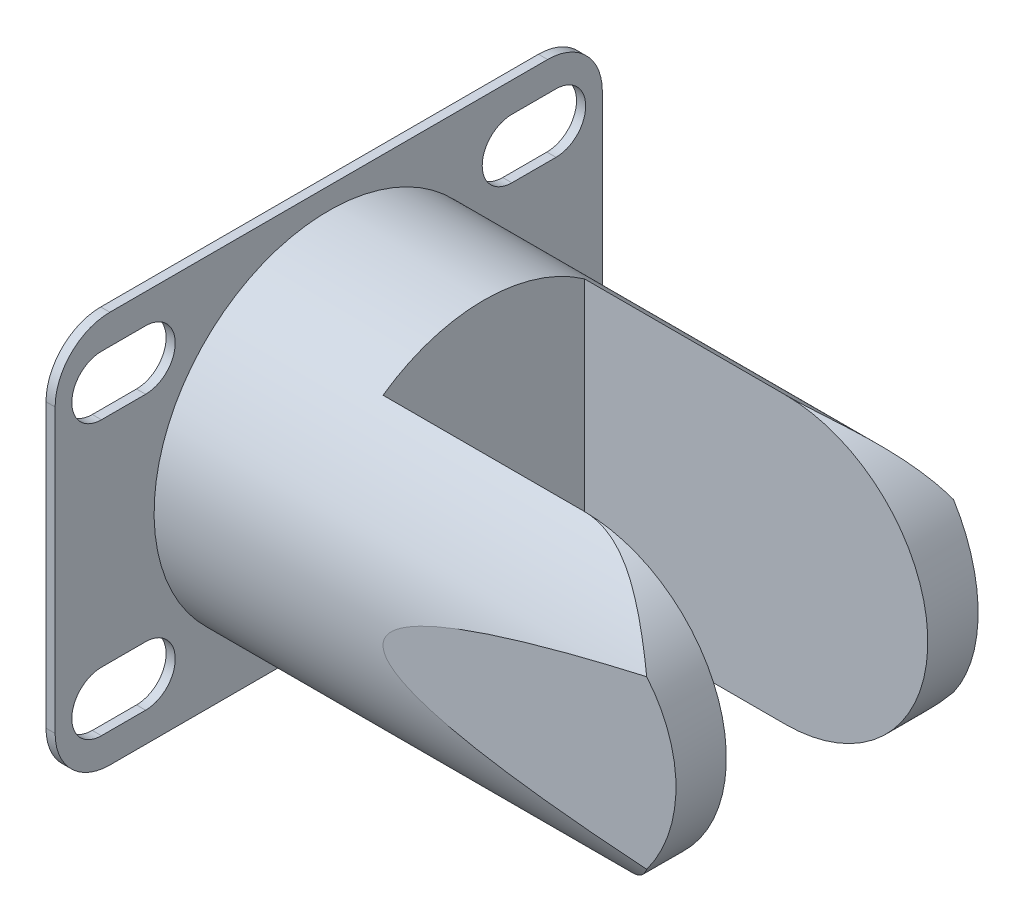
SolidWorks part; units mm, degrees
ref_plane "前视基准面" through (0, 0, 0) normal (0, 0, 1) x (1, 0, 0)
ref_plane "上视基准面" through (0, 0, 0) normal (0, 1, 0) x (1, 0, 0)
ref_plane "右视基准面" through (0, 0, 0) normal (1, 0, 0) x (0, 0, -1)
sketch "草图1" plane through (0, 0, 0) normal (1, 0, 0) x (0, 0, -1)
  line L0 (0, 0) -> (0, 13.3809) construction
  line L1 (-15.5, -30) -> (15.5, -30)
  line L2 (-21.5, -24) -> (-21.5, 24)
  line L3 (-15.5, 30) -> (15.5, 30)
  line L4 (21.5, -24) -> (21.5, 24)
  line L5 (-21.5, -30) -> (21.5, 30) construction
  line L6 (-21.5, 30) -> (21.5, -30) construction
  line L7 (0, 0) -> (10.4519, 0) construction
  circle A0 centre (15, 22.5) radius 1.5
  circle A1 centre (-15, 22.5) radius 1.5
  circle A2 centre (15, -22.5) radius 1.5
  circle A3 centre (-15, -22.5) radius 1.5
  arc A4 (-21.5, -24) -> (-15.5, -30) centre (-15.5, -24) ccw
  arc A5 (15.5, -30) -> (21.5, -24) centre (15.5, -24) ccw
  arc A6 (21.5, 24) -> (15.5, 30) centre (15.5, 24) ccw
  arc A7 (-15.5, 30) -> (-21.5, 24) centre (-15.5, 24) ccw
  point P0 (0, 0)
  dimension "D3" = 3
  dimension "D6" = 6
  dimension "D1" = 43
  dimension "D2" = 60
  dimension "D4" = 22.5
  dimension "D5" = 15
extrude "凸台-拉伸1" add sketch "草图1" along normal blind 1
sketch "草图2" plane through (1, 0, 0) normal (1, 0, 0) x (0, 0, -1)
  circle A0 centre (0, 0) radius 19.148
extrude "凸台-拉伸2" add sketch "草图2" along normal blind 59
sketch "草图3" plane through (60, 0, 0) normal (1, 0, 0) x (0, 0, -1)
  line L0 (0, 0) -> (0, 9.9455) construction
  line L1 (-34.2192, 20.5652) -> (-16.1825, 20.5652)
  line L2 (-34.2192, 20.5652) -> (-34.2192, -17.9524)
  line L3 (-34.2192, -17.9524) -> (-16.1825, -17.9524)
  line L4 (-16.1825, 20.5652) -> (-16.1825, -17.9524)
  line L5 (16.1825, 20.5652) -> (16.1825, -17.9524)
  line L6 (34.2192, -17.9524) -> (16.1825, -17.9524)
  line L7 (34.2192, 20.5652) -> (34.2192, -17.9524)
  line L8 (34.2192, 20.5652) -> (16.1825, 20.5652)
extrude "切除-拉伸1" cut sketch "草图3" against normal blind 56 draft 5
sketch "草图4" plane through (0, 0, 0) normal (0, 0, 1) x (1, 0, 0)
  line L0 (60, 0) -> (40, 0) construction
  line L1 (60, -10.2359) -> (60, 10.2359) construction
  circle A0 centre (40, 0) radius 20
  dimension "D1" = 20
extrude "凸台-拉伸3" add sketch "草图4" along normal mid plane 20 separate body
sketch "草图5" plane through (60, 0, 0) normal (1, 0, 0) x (0, 0, -1)
  line L1 (-11.0452, -21.6205) -> (11.0452, -21.6205)
  line L2 (-11.0452, -21.6205) -> (-11.0452, 21.6205)
  line L3 (-11.0452, 21.6205) -> (11.0452, 21.6205)
  line L4 (11.0452, -21.6205) -> (11.0452, 21.6205)
  line L5 (-11.0452, -21.6205) -> (11.0452, 21.6205) construction
  line L6 (-11.0452, 21.6205) -> (11.0452, -21.6205) construction
  point P0 (0, 0)
extrude "切除-拉伸2" cut sketch "草图5" against normal blind 42
sketch "草图6" plane through (0, 0, 0) normal (0, 0, 1) x (1, 0, 0)
  line L0 (40, 15.6413) -> (60, 15.6413)
  line L1 (60, 15.6413) -> (60, -15.6413)
  line L2 (60, -15.6413) -> (40, -15.6413)
  arc A0 (40, -15.6413) -> (40, 15.6413) centre (40, 0) ccw
extrude "切除-拉伸3" cut sketch "草图6" against normal through all both and the other way through all
sketch "草图7" plane through (0, 0, -21.5) normal (0, 0, -1) x (-1, 0, 0)
  line L0 (-1, 32.8673) -> (-1, -33.991)
split "分割1" trim tools "草图7" bodies to split 111 resulting bodies 112 113
move or copy body "实体-移动/复制1" bodies to move or copy 113 copy no rotation origin (0, 0, 0) rotation axis (1, 0, 0) rotation angle 90
delete or keep bodies "实体-删除/保留 1" type delete bodies bodies 109
sketch "草图8" plane through (0, 0, 0) normal (-1, 0, 0) x (0, 0, 1)
  line L0 (30, 0) -> (22.5, 0) construction
  line L1 (30, 15.5) -> (30, -15.5) construction
  line L2 (22.5, 0) -> (22.5, 15) construction
  line L3 (20.0787, 15) -> (24.9213, 15) construction
  line L4 (20.0787, 18.25) -> (24.9213, 18.25)
  line L5 (20.0787, 11.75) -> (24.9213, 11.75)
  line L6 (20.0787, -15) -> (24.9213, -15) construction
  line L7 (20.0787, -18.25) -> (24.9213, -18.25)
  line L8 (20.0787, -11.75) -> (24.9213, -11.75)
  line L9 (0, 0) -> (0, 6.5107) construction
  line L10 (-20.0787, -15) -> (-24.9213, -15) construction
  line L11 (-20.0787, -18.25) -> (-24.9213, -18.25)
  line L12 (-20.0787, -11.75) -> (-24.9213, -11.75)
  line L13 (-20.0787, 15) -> (-24.9213, 15) construction
  line L14 (-20.0787, 18.25) -> (-24.9213, 18.25)
  line L15 (-20.0787, 11.75) -> (-24.9213, 11.75)
  arc A0 (20.0787, 18.25) -> (20.0787, 11.75) centre (20.0787, 15) ccw
  arc A1 (24.9213, 11.75) -> (24.9213, 18.25) centre (24.9213, 15) ccw
  arc A2 (20.0787, -18.25) -> (20.0787, -11.75) centre (20.0787, -15) cw
  arc A3 (24.9213, -11.75) -> (24.9213, -18.25) centre (24.9213, -15) cw
  arc A4 (-20.0787, -18.25) -> (-20.0787, -11.75) centre (-20.0787, -15) ccw
  arc A5 (-24.9213, -11.75) -> (-24.9213, -18.25) centre (-24.9213, -15) ccw
  arc A6 (-20.0787, 18.25) -> (-20.0787, 11.75) centre (-20.0787, 15) cw
  arc A7 (-24.9213, 11.75) -> (-24.9213, 18.25) centre (-24.9213, 15) cw
  point P8 (22.5, 15)
  point P17 (22.5, -15)
  point P25 (-22.5, -15)
  point P32 (-22.5, 15)
  dimension "D2" = 3.25
  dimension "D1" = 7.5
extrude "切除-拉伸4" cut sketch "草图8" against normal blind 10
